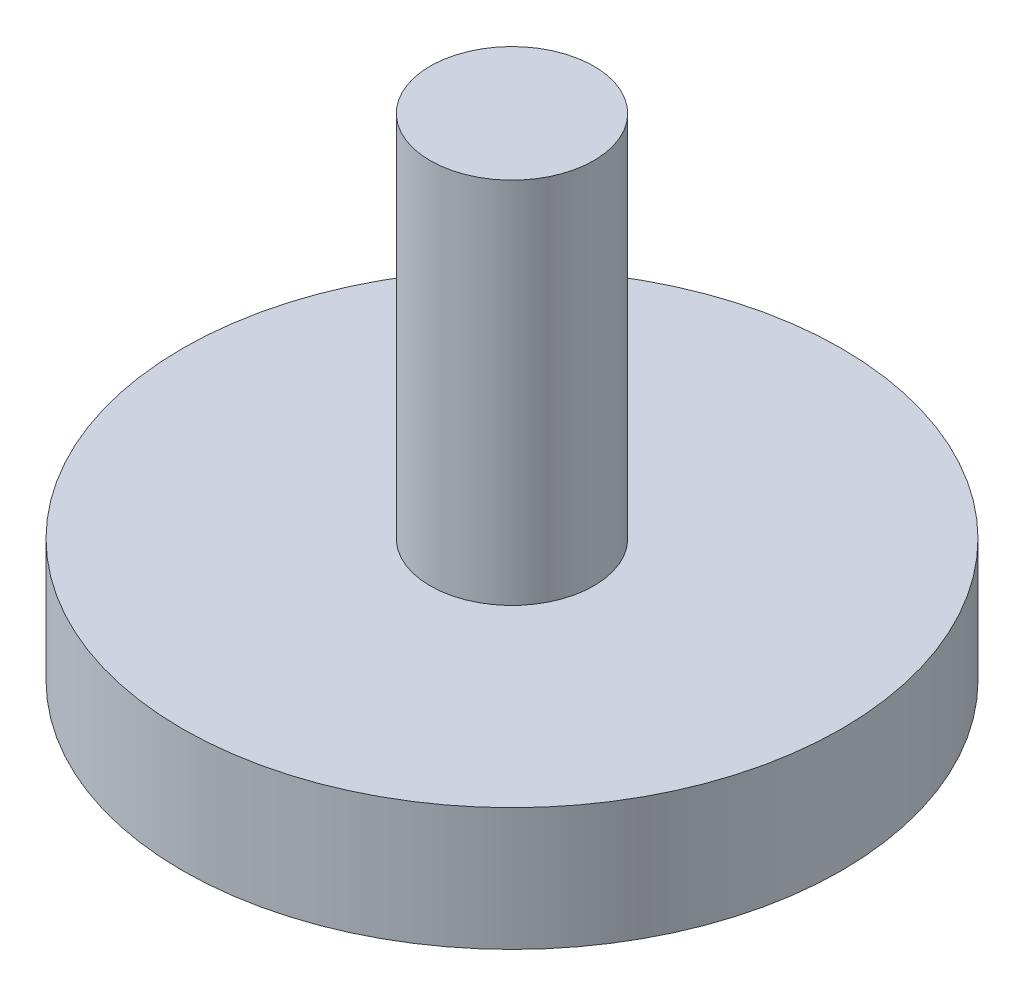
SolidWorks part; units mm, degrees
ref_plane "Front Plane" through (0, 0, 0) normal (0, 0, 1) x (1, 0, 0)
ref_plane "Top Plane" through (0, 0, 0) normal (0, 1, 0) x (1, 0, 0)
ref_plane "Right Plane" through (0, 0, 0) normal (1, 0, 0) x (0, 0, -1)
sketch "Sketch1" plane through (0, 0, 0) normal (0, 1, 0) x (1, 0, 0)
  circle A0 centre (0, 0) radius 51.1302
  dimension "D1" = 102.2604
extrude "Boss-Extrude1" add sketch "Sketch1" along normal mid plane 19.05 contours A0
sketch "Sketch2" plane through (0, 9.525, 0) normal (0, 1, 0) x (1, 0, 0)
  circle A0 centre (0, 0) radius 12.7
  dimension "D1" = 25.4
extrude "Boss-Extrude2" add sketch "Sketch2" along normal blind 57.15
